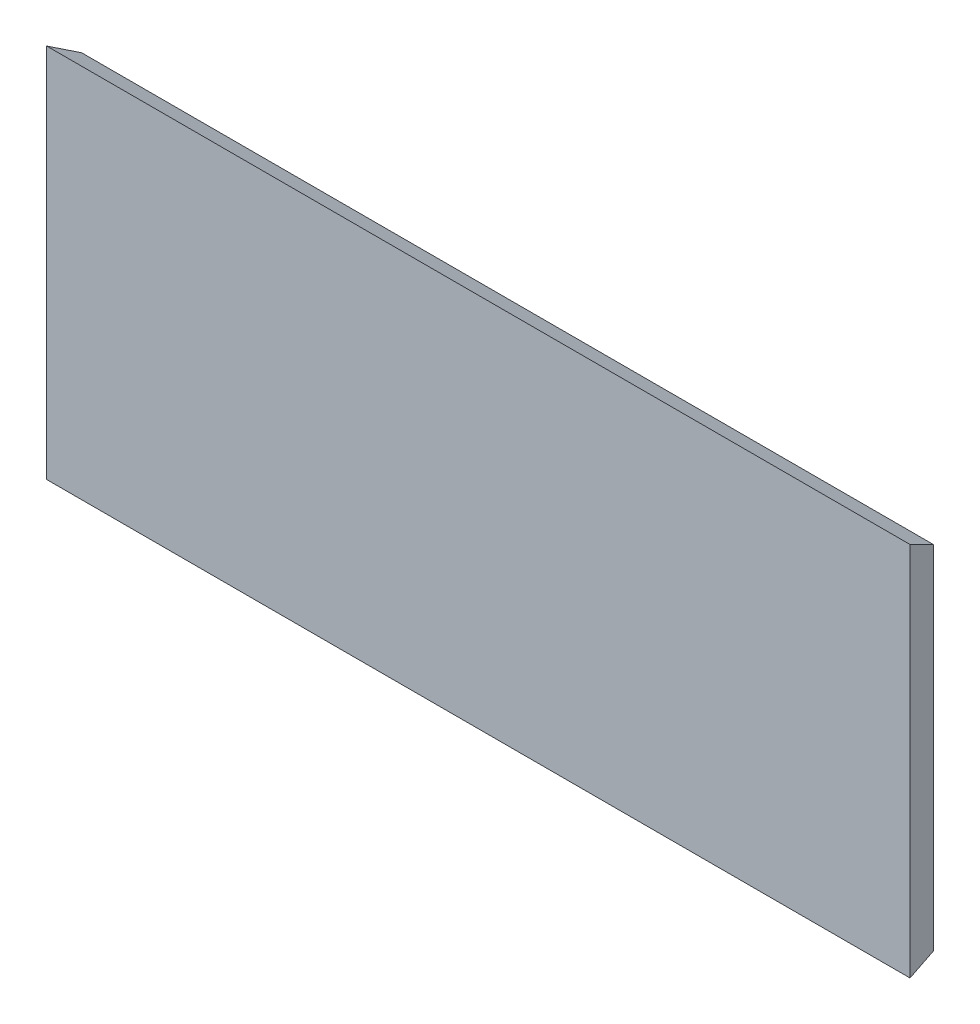
SolidWorks part; units mm, degrees
ref_plane "Front Plane" through (0, 0, 0) normal (0, 0, 1) x (1, 0, 0)
ref_plane "Top Plane" through (0, 0, 0) normal (0, 1, 0) x (1, 0, 0)
ref_plane "Right Plane" through (0, 0, 0) normal (1, 0, 0) x (0, 0, -1)
sketch "Sketch1" plane through (0, 0, 0) normal (0, 0, 1) x (1, 0, 0)
  line L1 (0, 0) -> (107.5, 0)
  line L2 (0, 0) -> (0, 23.5)
  line L3 (0, 23.5) -> (107.5, 23.5)
  line L4 (107.5, 0) -> (107.5, 23.5)
  dimension "D1" = 107.5
  dimension "D2" = 23.5
extrude "Boss-Extrude1" add sketch "Sketch1" along normal blind 3
sketch "Sketch2" plane through (107.5, 0, 0) normal (1, 0, 0) x (0, 0, -1)
  line L6 (-3.4236, 23.6) -> (0.1, 21.8382)
  line L7 (0.1, 23.6) -> (0.1, 21.8382)
  line L8 (0.1, 23.6) -> (-3.4236, 23.6)
extrude "Cut-Extrude1" cut sketch "Sketch2" against normal blind 109
sketch "Sketch3" plane through (0, 0, 0) normal (0, -1, 0) x (1, 0, 0)
  line L6 (-0.1, -0.1) -> (1.6618, -0.1)
  line L7 (1.6618, -0.1) -> (-0.1, 3.4241)
  line L8 (-0.1, -0.1) -> (-0.1, 3.4241)
extrude "Cut-Extrude2" cut sketch "Sketch3" against normal blind 23.5
sketch "Sketch4" plane through (0, 0, 3) normal (0, 0, 1) x (1, 0, 0)
  line L1 (0.112, 23.3882) -> (107.5, 23.3882)
  line L2 (0.112, 23.3882) -> (0.112, 0)
  line L3 (0.112, 0) -> (107.5, 0)
  line L4 (107.5, 23.3882) -> (107.5, 0)
extrude "Cut-Extrude3" cut sketch "Sketch4" against normal blind 0.1
mirror "Mirror2" about plane through (0, 0, 3) normal (0, 1, 0) of "Cut-Extrude3", "Cut-Extrude2", "Cut-Extrude1", "Boss-Extrude1"
